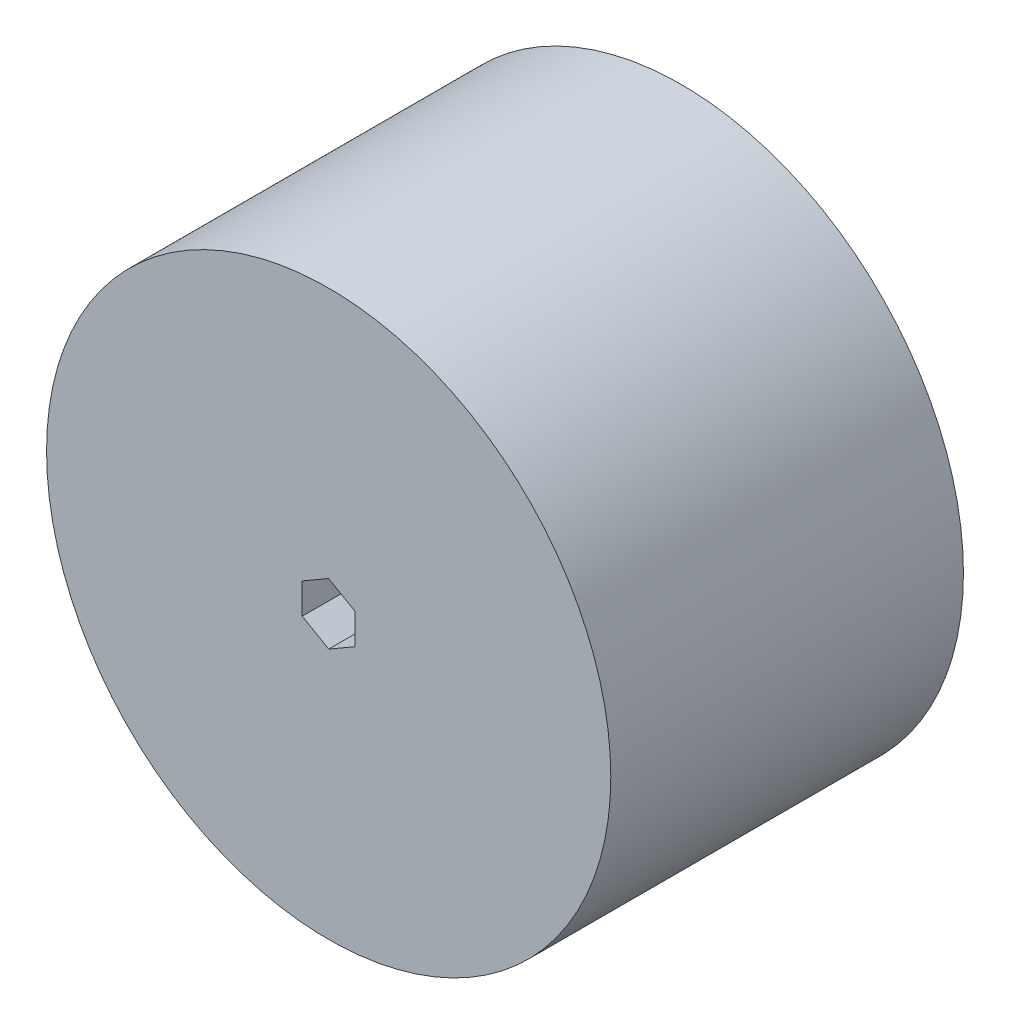
SolidWorks part; units mm, degrees
ref_plane "Front Plane" through (0, 0, 0) normal (0, 0, 1) x (1, 0, 0)
ref_plane "Top Plane" through (0, 0, 0) normal (0, 1, 0) x (1, 0, 0)
ref_plane "Right Plane" through (0, 0, 0) normal (1, 0, 0) x (0, 0, -1)
sketch "Sketch1" plane through (0, 0, 0) normal (0, 0, 1) x (1, 0, 0)
  line L1 (4.7603, 2.7535) -> (-0.0045, 5.4993)
  line L2 (-0.0045, 5.4993) -> (-4.7647, 2.7458)
  line L3 (-4.7647, 2.7458) -> (-4.7603, -2.7535)
  line L4 (-4.7603, -2.7535) -> (0.0045, -5.4993)
  line L5 (0.0045, -5.4993) -> (4.7647, -2.7458)
  line L6 (4.7647, -2.7458) -> (4.7603, 2.7535)
  circle A0 centre (0, 0) radius 50.8
  circle A1 centre (0, 0) radius 4.7625 construction
  dimension "D1" = 101.6
  dimension "D2" = 9.525
extrude "Boss-Extrude1" add sketch "Sketch1" along normal blind 63.5
